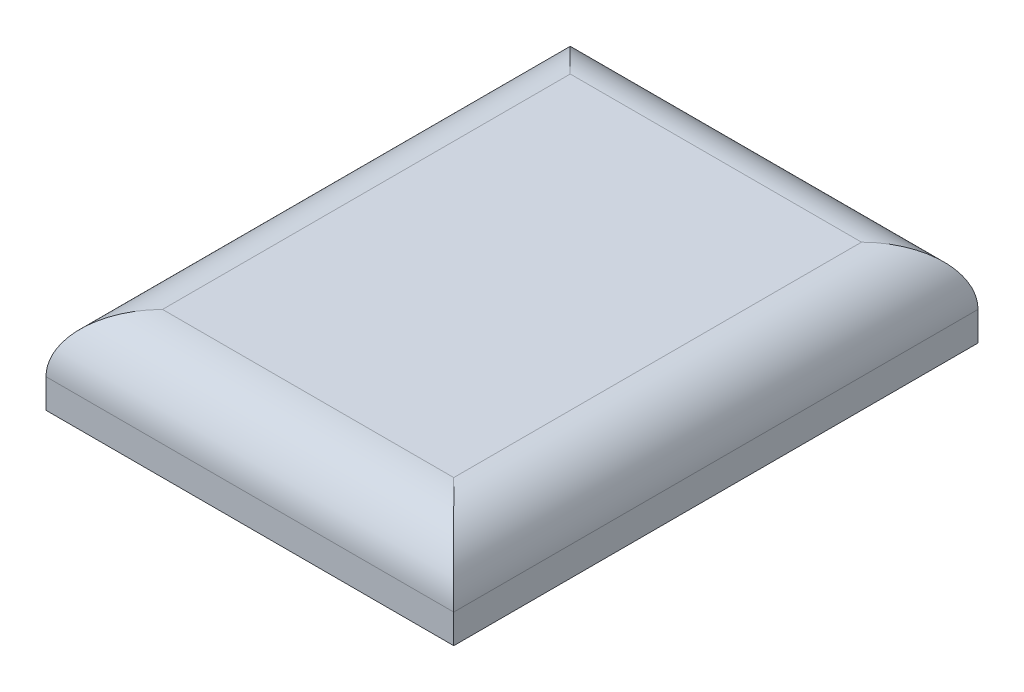
SolidWorks part; units mm, degrees
ref_plane "Front Plane" through (0, 0, 0) normal (0, 0, 1) x (1, 0, 0)
ref_plane "Top Plane" through (0, 0, 0) normal (0, 1, 0) x (1, 0, 0)
ref_plane "Right Plane" through (0, 0, 0) normal (1, 0, 0) x (0, 0, -1)
sketch "Sketch1" plane through (0, 0, 0) normal (0, 1, 0) x (1, 0, 0)
  line L1 (-35, -45) -> (35, -45)
  line L2 (-35, -45) -> (-35, 45)
  line L3 (-35, 45) -> (35, 45)
  line L4 (35, -45) -> (35, 45)
  line L5 (-35, -45) -> (35, 45) construction
  line L6 (-35, 45) -> (35, -45) construction
  point P0 (0, 0)
  dimension "D1" = 90
  dimension "D2" = 70
extrude "Boss-Extrude1" add sketch "Sketch1" along normal blind 15
fillet "Fillet1" radius 10 4 edges at (0, 15, -45) (-35, 15, 0) (0, 15, 45) (35, 15, 0)
